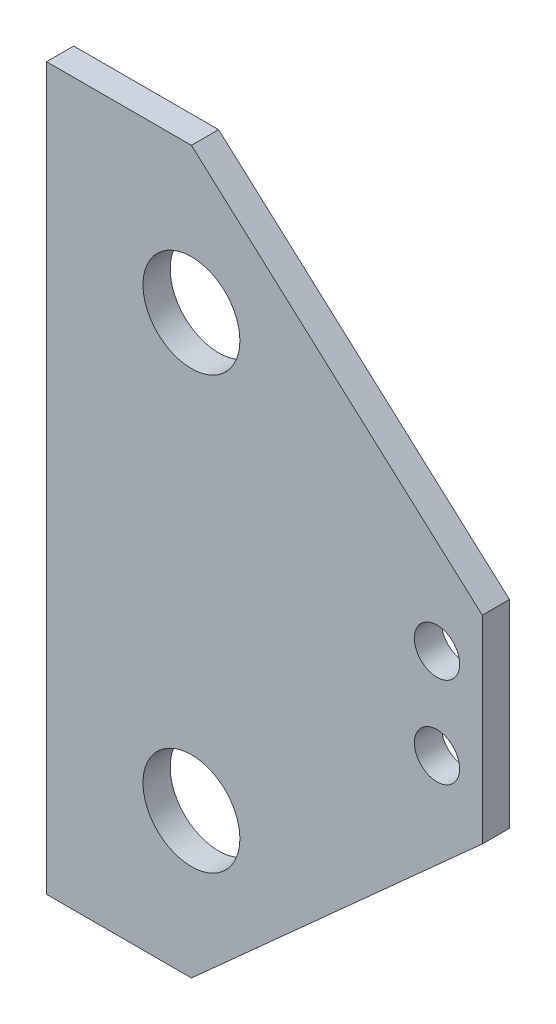
SolidWorks part; units mm, degrees
ref_plane "Front Plane" through (0, 0, 0) normal (0, 0, 1) x (1, 0, 0)
ref_plane "Top Plane" through (0, 0, 0) normal (0, 1, 0) x (1, 0, 0)
ref_plane "Right Plane" through (0, 0, 0) normal (1, 0, 0) x (0, 0, -1)
sketch "Sketch1" plane through (0, 0, 0) normal (0, 0, 1) x (1, 0, 0)
  line L0 (49.7243, -3.1916) -> (-39.1519, -3.1916) construction
  line L1 (-45.2241, 36.6234) -> (51.3119, 36.6234)
  line L2 (-45.2241, 36.6234) -> (-45.2241, -43.0066)
  line L3 (-45.2241, -43.0066) -> (51.3119, -43.0066)
  line L4 (51.3119, 36.6234) -> (51.3119, -43.0066)
  line L5 (-45.2241, 36.6234) -> (51.3119, -43.0066) construction
  line L6 (-45.2241, -43.0066) -> (51.3119, 36.6234) construction
  line L7 (17.6073, 20.6234) -> (17.6073, -27.0066) construction
  line L8 (1.6073, 36.6234) -> (1.6073, -43.0066)
  line L9 (17.6073, -43.0066) -> (51.6073, -12.4416)
  line L10 (17.6073, 36.6234) -> (51.6073, 6.0584)
  line L11 (49.7243, -14.1344) -> (49.7243, 7.7511)
  circle A0 centre (17.6073, 20.6234) radius 5.35
  circle A1 centre (17.6073, -27.0066) radius 5.35
  circle A2 centre (44.7243, 1.8084) radius 2.5
  circle A3 centre (44.7243, -8.1916) radius 2.5
  point P0 (3.0439, -3.1916)
  point P10 (17.6073, -3.1916)
  point P15 (1.6073, -3.1916)
  dimension "D2" = 10.7
  dimension "D3" = 10.7
  dimension "D6" = 5
  dimension "D7" = 5
  dimension "D10" = 5
  dimension "D11" = 5
  dimension "D1" = 47.63
  dimension "D4" = 16
  dimension "D5" = 16
  dimension "D8" = 5
  dimension "D9" = 5
extrude "Boss-Extrude1" add sketch "Sketch1" along normal blind 3 contours L9 L11 L10 L1 L8 L3 A3 A2 A1 A0
